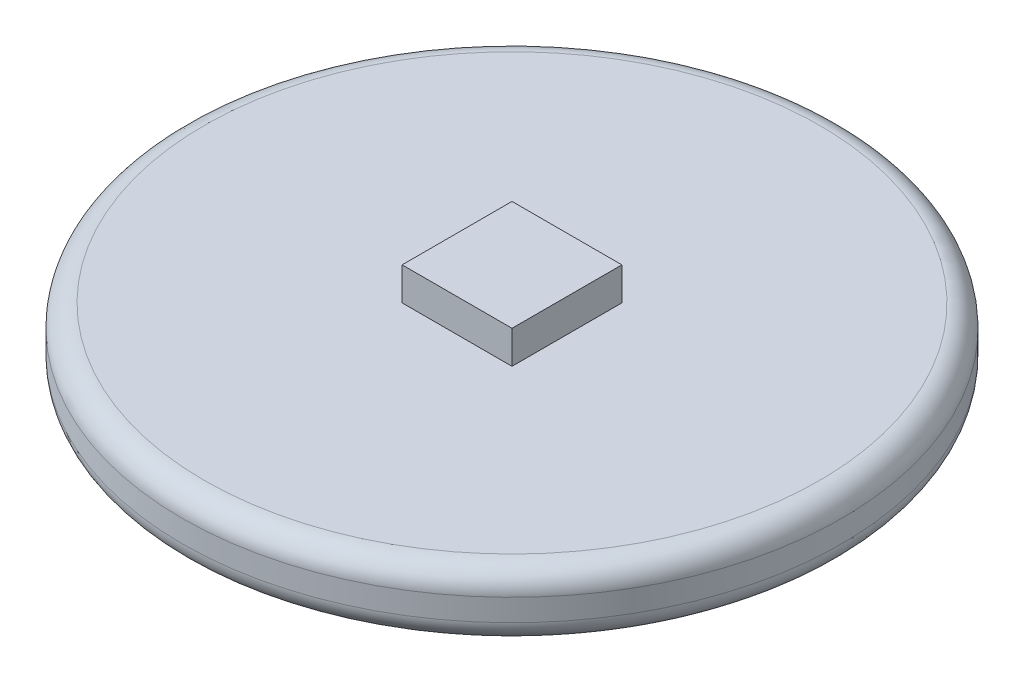
SolidWorks part; units mm, degrees
ref_plane "Front Plane" through (0, 0, 0) normal (0, 0, 1) x (1, 0, 0)
ref_plane "Top Plane" through (0, 0, 0) normal (0, 1, 0) x (1, 0, 0)
ref_plane "Right Plane" through (0, 0, 0) normal (1, 0, 0) x (0, 0, -1)
sketch "Sketch1" plane through (0, 0, 0) normal (0, 1, 0) x (1, 0, 0)
  circle A0 centre (0, 0) radius 30
  dimension "D1" = 60
extrude "Boss-Extrude1" add sketch "Sketch1" along normal blind 6
fillet "Fillet2" radius 2 2 edges at (0, 0, 30) (0, 6, 30)
sketch "Sketch3" plane through (0, 6, 0) normal (0, 1, 0) x (1, 0, 0)
  line L1 (5, -5) -> (-5, -5)
  line L2 (5, -5) -> (5, 5)
  line L3 (5, 5) -> (-5, 5)
  line L4 (-5, -5) -> (-5, 5)
  line L5 (5, -5) -> (-5, 5) construction
  line L6 (5, 5) -> (-5, -5) construction
  point P0 (0, 0)
  dimension "D1" = 10
  dimension "D2" = 10
extrude "Boss-Extrude3" add sketch "Sketch3" along normal blind 3
